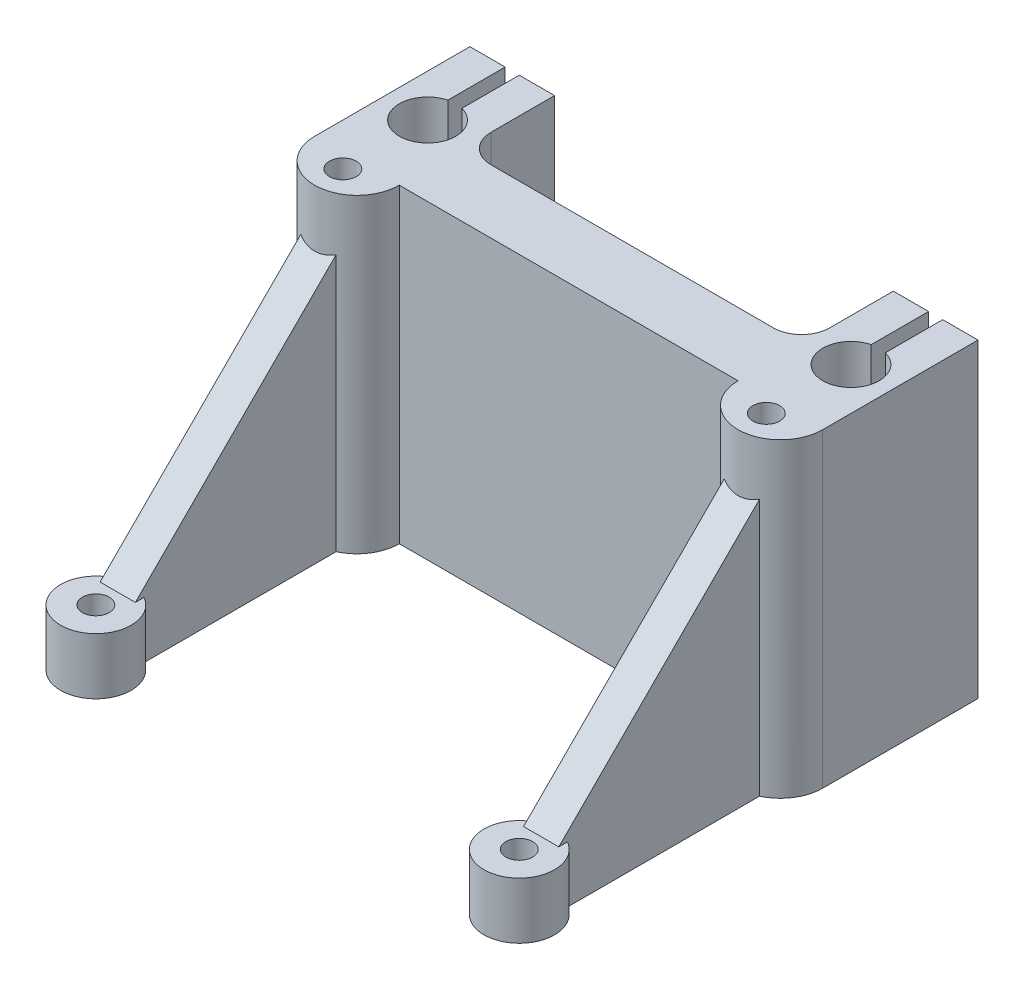
SolidWorks part; units mm, degrees
material "ABS"
ref_plane "Front Plane" through (0, 0, 0) normal (0, 0, 1) x (1, 0, 0)
ref_plane "Top Plane" through (0, 0, 0) normal (0, 1, 0) x (1, 0, 0)
ref_plane "Right Plane" through (0, 0, 0) normal (1, 0, 0) x (0, 0, -1)
sketch "Sketch1" plane through (0, 0, 0) normal (0, 1, 0) x (1, 0, 0)
  line L0 (0, 12) -> (0, -10) construction
  line L1 (-24, -10) -> (24, -10)
  line L2 (-36, -10) -> (-36, 12)
  line L3 (-36, 12) -> (36, 12)
  line L4 (36, -10) -> (36, 12)
  line L5 (0, 1) -> (36, 12) construction
  line L6 (0, 1) -> (36, -10) construction
  arc A0 (24, -10) -> (36, -10) centre (30, -10) ccw
  arc A1 (-24, -10) -> (-36, -10) centre (-30, -10) cw
  point P0 (0, 1)
  dimension "D4" = 12
  dimension "D1" = 36
  dimension "D2" = 22
  dimension "D3" = 30
  dimension "D5" = 1
extrude "Boss-Extrude1" add sketch "Sketch1" along normal blind 44
sketch "Sketch3" plane through (0, 44, 0) normal (0, 1, 0) x (1, 0, 0)
  circle A0 centre (-30, 0) radius 4
  circle A1 centre (-30, -12) radius 1.9
  dimension "D2" = 8
  dimension "D4" = 3.8
  dimension "D1" = 30
  dimension "D3" = 12
extrude "Cut-Extrude1" cut sketch "Sketch3" against normal through all
sketch "Sketch4" plane through (0, 44, 0) normal (0, 1, 0) x (1, 0, 0)
  line L0 (36, 12) -> (-36, 12) construction
  line L1 (-31, 12) -> (-29, 12)
  line L2 (-31, 12) -> (-31, 0)
  line L3 (-31, 0) -> (-29, 0)
  line L4 (-29, 12) -> (-29, 0)
  line L5 (-31, 12) -> (-29, 0) construction
  line L6 (-31, 0) -> (-29, 12) construction
  point P0 (-30, 6)
  point P5 (-30, 0)
  dimension "D1" = 2
extrude "Cut-Extrude2" cut sketch "Sketch4" against normal through all
mirror "Mirror1" about plane through (0, 0, 0) normal (1, 0, 0) of "Cut-Extrude2", "Cut-Extrude1"
sketch "Sketch5" plane through (0, 44, 0) normal (0, 1, 0) x (1, 0, 0)
  line L0 (29, 12) -> (-29, 12) construction
  line L1 (-24, -1) -> (24, -1)
  line L2 (-24, -1) -> (-24, 12)
  line L3 (-24, 12) -> (24, 12)
  line L4 (24, -1) -> (24, 12)
  line L5 (-24, -1) -> (24, 12) construction
  line L6 (-24, 12) -> (24, -1) construction
  point P0 (0, 5.5)
  dimension "D1" = 48
  dimension "D2" = 1
extrude "Cut-Extrude3" cut sketch "Sketch5" against normal through all
ref_plane "Plane1" through (-30, 0, 0) normal (-1, 0, 0) x (0, 0, 1)
fillet "Fillet1" radius 4 2 edges at (24, 22, 1) (-24, 22, 1)
sketch "Sketch8" plane through (-30, 0, 0) normal (-1, 0, 0) x (0, 0, 1)
  line L0 (43.9, 0) -> (13.9, 0)
  line L2 (13.9, 0) -> (13.9, 38)
  line L3 (13.9, 38) -> (43.9, 8)
  line L5 (43.9, 8) -> (43.9, 0)
  line L6 (13.9, 0) -> (13.9, 44) construction
  dimension "D1" = 30
  dimension "D2" = 45
  dimension "D3" = 38
extrude "Boss-Extrude5" add sketch "Sketch8" along normal mid plane 5
sketch "Sketch6" plane through (0, 0, 0) normal (0, 1, 0) x (1, 0, 0)
  line L0 (0, 0) -> (0, -43.0129) construction
  circle A0 centre (-30, -47) radius 5
  circle A1 centre (30, -47) radius 5
  point P2 (-30, -12)
  dimension "D2" = 10
  dimension "D1" = 47
extrude "Boss-Extrude2" add sketch "Sketch6" along normal blind 8 separate body
sketch "Sketch7" plane through (0, 8, 0) normal (0, 1, 0) x (1, 0, 0)
  line L0 (0, -1000) -> (0, 49000) construction
  circle A0 centre (-30, -47) radius 1.9
  circle A1 centre (30, -47) radius 1.9
  dimension "D1" = 3.8
mirror "Mirror7" about plane through (0, 0, 0) normal (1, 0, 0) of "Boss-Extrude5"
extrude "Cut-Extrude5" cut sketch "Sketch7" against normal through all
